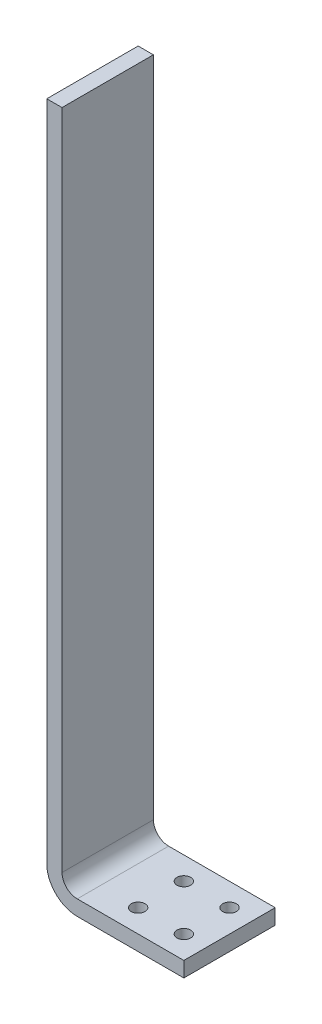
SolidWorks part; units mm, degrees
ref_plane "Front Plane" through (0, 0, 0) normal (0, 0, 1) x (1, 0, 0)
ref_plane "Top Plane" through (0, 0, 0) normal (0, 1, 0) x (1, 0, 0)
ref_plane "Right Plane" through (0, 0, 0) normal (1, 0, 0) x (0, 0, -1)
sketch "Sketch1" plane through (0, 0, 0) normal (0, 0, 1) x (1, 0, 0)
  line L0 (0, 20) -> (0, 455)
  line L1 (20, 0) -> (90, 0)
  line L2 (20, 10) -> (90, 10)
  line L3 (10, 20) -> (10, 455)
  line L4 (90, 10) -> (90, 0)
  line L5 (10, 455) -> (0, 455)
  arc A0 (0, 20) -> (20, 0) centre (20, 20) ccw
  arc A1 (10, 20) -> (20, 10) centre (20, 20) ccw
  point P6 (0, 0)
  dimension "D3" = 20
  dimension "D1" = 455
  dimension "D2" = 90
  dimension "D4" = 10
extrude "Boss-Extrude1" add sketch "Sketch1" along normal blind 60
sketch "Sketch2" plane through (0, 10, 0) normal (0, 1, 0) x (1, 0, 0)
  line L3 (90, -60) -> (90, 0) construction
  line L4 (90, 0) -> (20, 0) construction
  circle A3 centre (75, -15) radius 4.5
  circle A4 centre (75, -45) radius 4.5
  circle A5 centre (45, -15) radius 4.5
  circle A6 centre (45, -45) radius 4.5
  dimension "D1" = 9
  dimension "D2" = 15
  dimension "D3" = 15
  dimension "D4" = 15
  dimension "D5" = 30
  dimension "D6" = 30
  dimension "D7" = 15
  dimension "D8" = 0
  dimension "D9" = 30
extrude "Cut-Extrude1" cut sketch "Sketch2" against normal up to next
